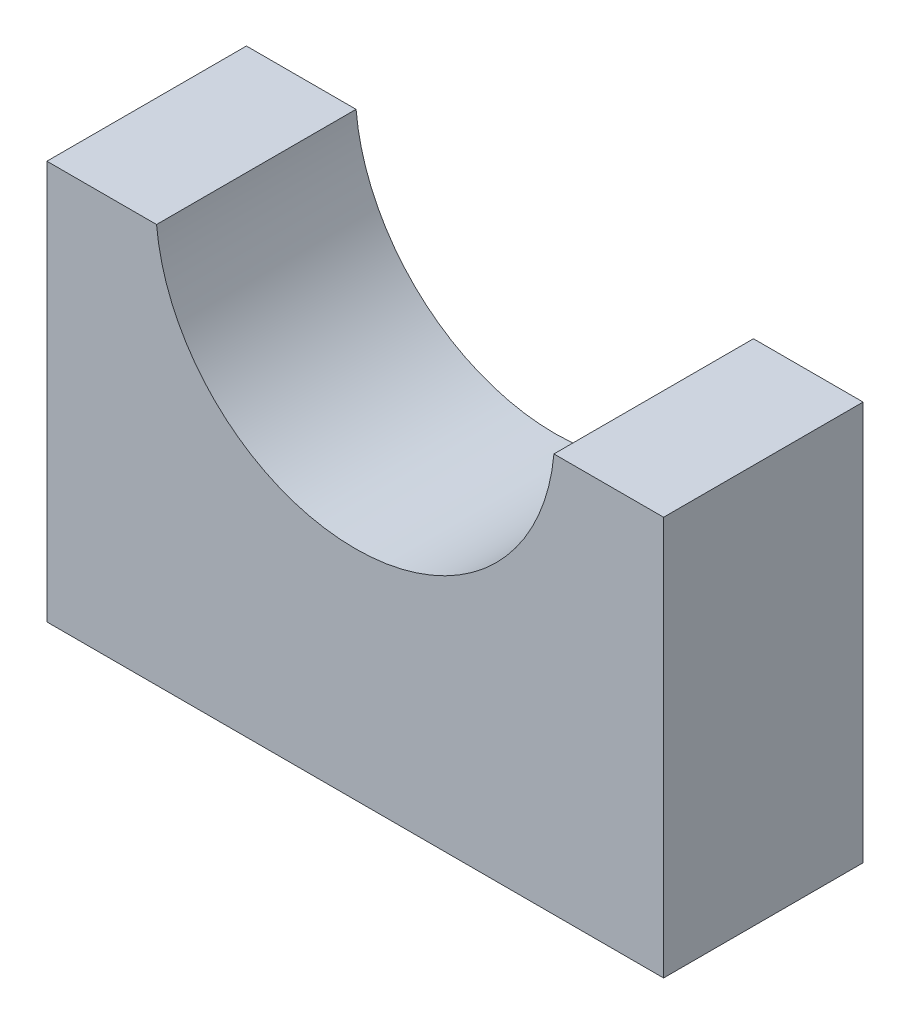
SolidWorks part; units mm, degrees
ref_plane "Front Plane" through (0, 0, 0) normal (0, 0, 1) x (1, 0, 0)
ref_plane "Top Plane" through (0, 0, 0) normal (0, 1, 0) x (1, 0, 0)
ref_plane "Right Plane" through (0, 0, 0) normal (1, 0, 0) x (0, 0, -1)
sketch "Sketch1" plane through (0, 0, 0) normal (0, 0, 1) x (1, 0, 0)
  line L0 (-17, 0) -> (17, 0) construction
  line L1 (0, 0) -> (0, -11) construction
  line L2 (-17, -1) -> (17, -1)
  line L4 (-17, -1) -> (-17, -23)
  line L5 (-17, -23) -> (17, -23)
  line L6 (17, -23) -> (17, -1)
  circle A0 centre (0, 0) radius 11
  dimension "D1" = 22
  dimension "D2" = 17
  dimension "D5" = 22
  dimension "D3" = 1
extrude "Boss-Extrude1" add sketch "Sketch1" along normal blind 11 contours A0 L2 L4 L5 L6
